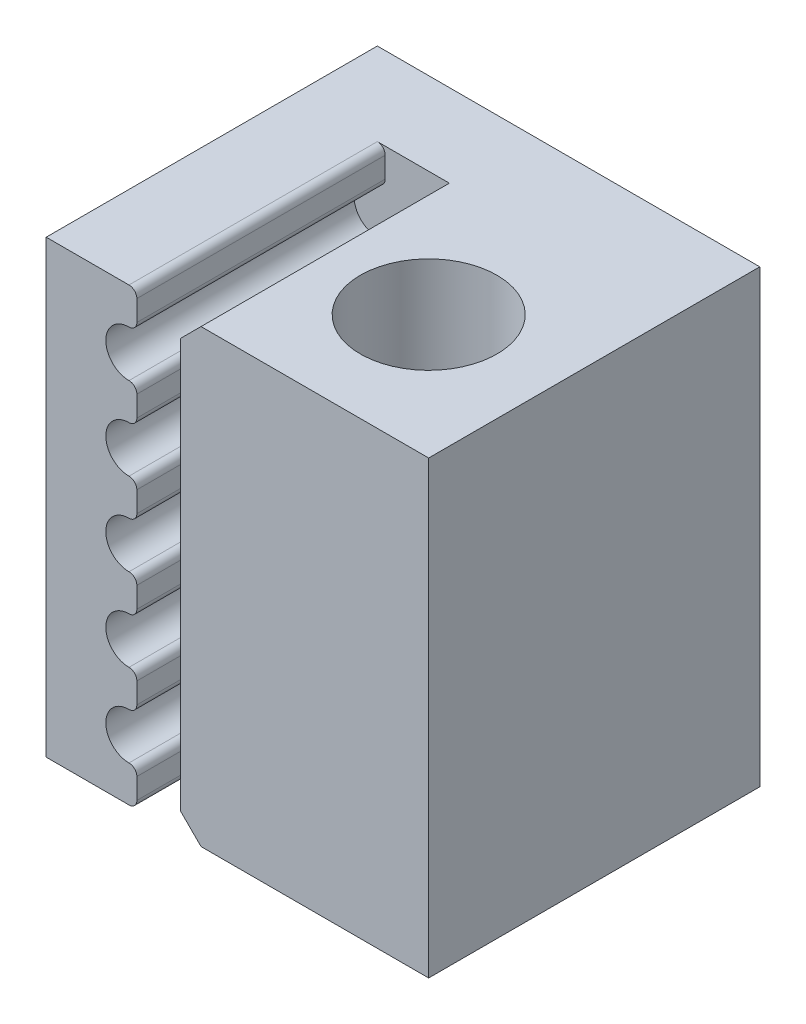
SolidWorks part; units mm, degrees
material "ABS"
ref_plane "Ebene vorne" through (0, 0, 0) normal (0, 0, 1) x (1, 0, 0)
ref_plane "Ebene oben" through (0, 0, 0) normal (0, 1, 0) x (1, 0, 0)
ref_plane "Ebene rechts" through (0, 0, 0) normal (1, 0, 0) x (0, 0, -1)
sketch "Skizze1" plane through (0, 0, 0) normal (0, 0, 1) x (1, 0, 0)
  line L0 (0, 0) -> (0, 9.44)
  line L1 (0, 9.44) -> (-7.24, 9.44) construction
  line L2 (-7.05, 10.19) -> (-7.05, 10.69)
  line L3 (-7.05, 8.69) -> (-7.05, 8.19)
  line L4 (-7.24, 10.88) -> (-9.24, 10.88)
  line L5 (-9.24, 10.88) -> (-9.24, 0)
  line L6 (-7.05, 6.69) -> (-7.05, 6.19)
  line L7 (-7.05, 4.69) -> (-7.05, 4.19)
  line L8 (-7.05, 2.69) -> (-7.05, 2.19)
  line L9 (-7.05, 0.69) -> (-7.05, 0.19)
  line L10 (-7.05, -1.31) -> (-7.05, -1.81) construction
  line L11 (-7.05, -3.31) -> (-7.05, -3.81) construction
  line L12 (-7.05, -5.31) -> (-7.05, -5.81) construction
  line L13 (-7.05, -7.31) -> (-7.05, -7.81) construction
  line L14 (-7.05, -9.31) -> (-7.05, -9.81) construction
  line L15 (-7.24, 0) -> (-9.24, 0)
  line L16 (0, 9.44) -> (0, 10.88)
  line L17 (0, 10.88) -> (-6, 10.88)
  line L18 (-6, 10.88) -> (-6, 0)
  line L19 (-6, 0) -> (0, 0)
  arc A0 (-7.24, 10) -> (-7.24, 8.88) centre (-7.24, 9.44) ccw
  arc A1 (-7.24, 8) -> (-7.24, 6.88) centre (-7.24, 7.44) ccw
  arc A2 (-7.05, 8.69) -> (-7.24, 8.88) centre (-7.24, 8.69) ccw
  arc A3 (-7.24, 8) -> (-7.05, 8.19) centre (-7.24, 8.19) ccw
  arc A4 (-7.05, 10.19) -> (-7.24, 10) centre (-7.24, 10.19) cw
  arc A5 (-7.24, 10.88) -> (-7.05, 10.69) centre (-7.24, 10.69) cw
  arc A6 (-7.24, 8) -> (-7.24, 6.88) centre (-7.24, 7.44) ccw
  arc A7 (-7.05, 6.69) -> (-7.24, 6.88) centre (-7.24, 6.69) ccw
  arc A8 (-7.24, 6) -> (-7.05, 6.19) centre (-7.24, 6.19) ccw
  arc A9 (-7.24, 6) -> (-7.24, 4.88) centre (-7.24, 5.44) ccw
  arc A10 (-7.05, 4.69) -> (-7.24, 4.88) centre (-7.24, 4.69) ccw
  arc A11 (-7.24, 4) -> (-7.05, 4.19) centre (-7.24, 4.19) ccw
  arc A12 (-7.24, 4) -> (-7.24, 2.88) centre (-7.24, 3.44) ccw
  arc A13 (-7.05, 2.69) -> (-7.24, 2.88) centre (-7.24, 2.69) ccw
  arc A14 (-7.24, 2) -> (-7.05, 2.19) centre (-7.24, 2.19) ccw
  arc A15 (-7.24, 2) -> (-7.24, 0.88) centre (-7.24, 1.44) ccw
  arc A16 (-7.05, 0.69) -> (-7.24, 0.88) centre (-7.24, 0.69) ccw
  arc A17 (-7.24, 0) -> (-7.05, 0.19) centre (-7.24, 0.19) ccw
  arc A18 (-7.24, 0) -> (-7.24, -1.12) centre (-7.24, -0.56) ccw construction
  arc A19 (-7.05, -1.31) -> (-7.24, -1.12) centre (-7.24, -1.31) ccw construction
  arc A20 (-7.24, -2) -> (-7.05, -1.81) centre (-7.24, -1.81) ccw construction
  arc A21 (-7.24, -2) -> (-7.24, -3.12) centre (-7.24, -2.56) ccw construction
  arc A22 (-7.05, -3.31) -> (-7.24, -3.12) centre (-7.24, -3.31) ccw construction
  arc A23 (-7.24, -4) -> (-7.05, -3.81) centre (-7.24, -3.81) ccw construction
  arc A24 (-7.24, -4) -> (-7.24, -5.12) centre (-7.24, -4.56) ccw construction
  arc A25 (-7.05, -5.31) -> (-7.24, -5.12) centre (-7.24, -5.31) ccw construction
  arc A26 (-7.24, -6) -> (-7.05, -5.81) centre (-7.24, -5.81) ccw construction
  arc A27 (-7.24, -6) -> (-7.24, -7.12) centre (-7.24, -6.56) ccw construction
  arc A28 (-7.05, -7.31) -> (-7.24, -7.12) centre (-7.24, -7.31) ccw construction
  arc A29 (-7.24, -8) -> (-7.05, -7.81) centre (-7.24, -7.81) ccw construction
  arc A30 (-7.24, -8) -> (-7.24, -9.12) centre (-7.24, -8.56) ccw construction
  arc A31 (-7.05, -9.31) -> (-7.24, -9.12) centre (-7.24, -9.31) ccw construction
  arc A32 (-7.24, -10) -> (-7.05, -9.81) centre (-7.24, -9.81) ccw construction
  point P6 (-7.8, 9.44)
  dimension "D1" = 0.56
  dimension "D3" = 0.75
  dimension "D2" = 2
  dimension "D5" = 2
  dimension "D6" = 1.8
  dimension "D7" = 6
  dimension "D8" = 10.88
  dimension "D4" = 10
extrude "Aufsatz-Linear austragen1" add sketch "Skizze1" along normal blind 6
sketch "Skizze4" plane through (0, 0, 0) normal (0, 0, -1) x (-1, 0, 0)
  line L0 (9.24, 10.88) -> (9.24, 0) construction
  line L1 (0, 10.88) -> (9.24, 10.88)
  line L2 (0, 10.88) -> (0, 0)
  line L3 (0, 0) -> (9.24, 0)
  line L4 (9.24, 10.88) -> (9.24, 0)
extrude "Aufsatz-Linear austragen2" add sketch "Skizze4" along normal blind 2
sketch "Skizze3" plane through (0, 10.88, 0) normal (0, 1, 0) x (1, 0, 0)
  line L0 (0, -6) -> (-6, 0) construction
  circle A0 centre (-3, -3) radius 1.65
  dimension "D1" = 3.3
extrude "Schnitt-Linear austragen1" cut sketch "Skizze3" against normal up to surface (10.88 mm away) up to face at (-5.5425, 0, 2.875)
chamfer "Fase1" distance 0.5 angle 45 2 edges at (-6, 0, 3) (-6, 10.88, 3)
